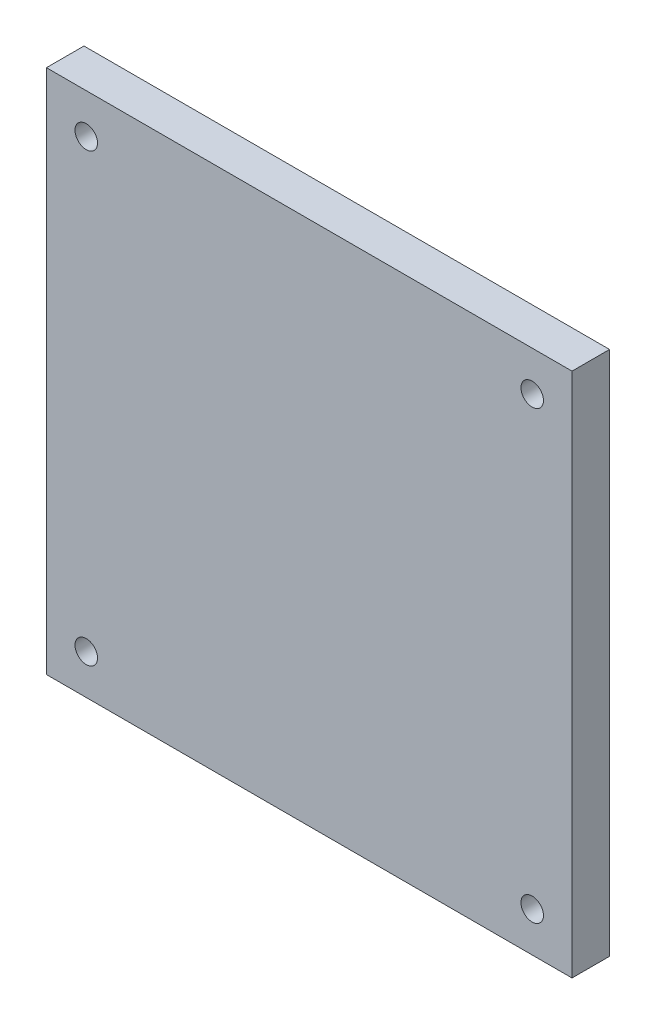
SolidWorks part; units mm, degrees
ref_plane "Спереди" through (0, 0, 0) normal (0, 0, 1) x (1, 0, 0)
ref_plane "Сверху" through (0, 0, 0) normal (0, 1, 0) x (1, 0, 0)
ref_plane "Справа" through (0, 0, 0) normal (1, 0, 0) x (0, 0, -1)
other "Configuration Table"
sketch "Эскиз1" plane through (0, 0, 0) normal (0, 0, 1) x (1, 0, 0)
  line L1 (35, -35) -> (-35, -35)
  line L2 (35, -35) -> (35, 35)
  line L3 (35, 35) -> (-35, 35)
  line L4 (-35, -35) -> (-35, 35)
  line L5 (35, -35) -> (-35, 35) construction
  line L6 (35, 35) -> (-35, -35) construction
  point P0 (0, 0)
  dimension "D1" = 70
  dimension "D2" = 70
extrude "Бобышка-Вытянуть1" add sketch "Эскиз1" along normal blind 5
sketch "Эскиз2" plane through (0, 0, 5) normal (0, 0, 1) x (1, 0, 0)
  line L0 (-35, 35) -> (-35, 20)
  line L2 (-20, 35) -> (-35, 35)
  line L3 (35, 35) -> (20, 35)
  line L4 (35, 20) -> (35, 35)
  line L5 (35, -35) -> (35, -20)
  line L6 (20, -35) -> (35, -35)
  line L7 (-35, -35) -> (-20, -35)
  line L8 (-35, -20) -> (-35, -35)
  line L9 (-35, 35) -> (-24.3934, 24.3934) construction
  line L10 (35, 35) -> (24.3934, 24.3934) construction
  line L11 (35, -35) -> (24.3934, -24.3934) construction
  line L12 (-35, -35) -> (-24.3934, -24.3934) construction
  arc A0 (-35, 20) -> (-20, 35) centre (-35, 35) ccw
  arc A1 (20, 35) -> (35, 20) centre (35, 35) ccw
  arc A2 (35, -20) -> (20, -35) centre (35, -35) ccw
  arc A3 (-20, -35) -> (-35, -20) centre (-35, -35) ccw
  circle A4 centre (-29.6967, 29.6967) radius 1.5
  circle A5 centre (29.6967, 29.6967) radius 1.5
  circle A6 centre (29.6967, -29.6967) radius 1.5
  circle A7 centre (-29.6967, -29.6967) radius 1.5
  point P16 (0, 0)
  point P32 (0, 0)
  dimension "D1" = 30
  dimension "D3" = 3
  dimension "D2" = 4
  dimension "D4" = 4
extrude "Вырез-Вытянуть1" cut sketch "Эскиз2" against normal blind 5 contours A4 | A5 | A6 | A7
